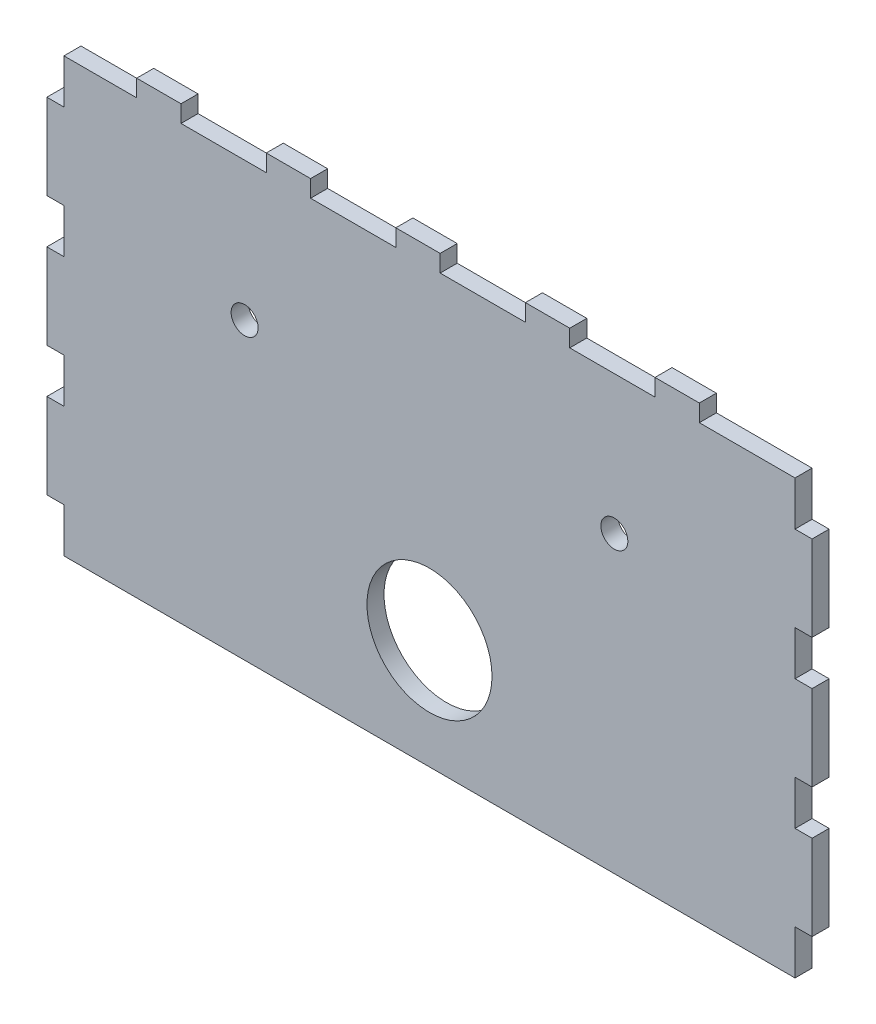
SolidWorks part; units mm, degrees
material "ENPH 253 Hardboard"
ref_plane "Front Plane" through (0, 0, 0) normal (0, 0, 1) x (1, 0, 0)
ref_plane "Top Plane" through (0, 0, 0) normal (0, 1, 0) x (1, 0, 0)
ref_plane "Right Plane" through (0, 0, 0) normal (1, 0, 0) x (0, 0, -1)
sketch "Sketch1" plane through (0, 0, 0) normal (0, 0, 1) x (1, 0, 0)
  line L1 (-67.32, 38.1) -> (67.32, 38.1)
  line L2 (-67.32, 38.1) -> (-67.32, -38.1)
  line L3 (-67.32, -38.1) -> (67.32, -38.1)
  line L4 (67.32, 38.1) -> (67.32, -38.1)
  line L5 (-67.32, 38.1) -> (67.32, -38.1) construction
  line L6 (-67.32, -38.1) -> (67.32, 38.1) construction
  point P0 (0, 0)
  dimension "D1" = 134.64
  dimension "D2" = 76.2
extrude "Boss-Extrude1" add sketch "Sketch1" along normal blind 3
sketch "Sketch2" plane through (0, 0, 3) normal (0, 0, 1) x (1, 0, 0)
  line L1 (-67.32, 38.1) -> (-64.32, 38.1)
  line L2 (-67.32, 38.1) -> (-67.32, 30.3)
  line L3 (-67.32, 30.3) -> (-64.32, 30.3)
  line L4 (-64.32, 38.1) -> (-64.32, 30.3)
  dimension "D1" = 3
  dimension "D2" = 7.8
extrude "Cut-Extrude1" cut sketch "Sketch2" against normal through all
pattern_linear "LPattern1" count 4 spacing 22.8 along (0, -1, 0) of "Cut-Extrude1"
mirror "Mirror4" about plane through (0, 0, 0) normal (1, 0, 0) of "LPattern1", "Cut-Extrude1"
sketch "Sketch3" plane through (0, 38.1, 0) normal (0, 1, 0) x (1, 0, 0)
  line L0 (64.32, 0) -> (-64.32, 0) construction
  line L1 (-43.72, 0) -> (-51.52, 0)
  line L2 (-43.72, 0) -> (-43.72, -3)
  line L3 (-43.72, -3) -> (-51.52, -3)
  line L4 (-51.52, 0) -> (-51.52, -3)
  line L5 (64.32, -3) -> (-64.32, -3) construction
  line L6 (-64.32, 0) -> (-64.32, -3) construction
  dimension "D1" = 12.8
  dimension "D2" = 7.8
extrude "Boss-Extrude2" add sketch "Sketch3" along normal blind 3
pattern_linear "LPattern2" count 5 spacing 22.8 along (1, 0, 0) of "Boss-Extrude2"
sketch "Sketch4" plane through (0, 0, 3) normal (0, 0, 1) x (1, 0, 0)
  line L0 (-64.32, -38.1) -> (64.32, -38.1) construction
  line L1 (-64.32, -38.1) -> (-64.32, -30.3) construction
  circle A0 centre (0, -18.8) radius 11
  dimension "D1" = 22
  dimension "D2" = 19.3
  dimension "D3" = 64.32
extrude "Cut-Extrude2" cut sketch "Sketch4" against normal through all
sketch "Sketch5" plane through (0, 0, 3) normal (0, 0, 1) x (1, 0, 0)
  line L0 (0, -18.8) -> (-36.8059, -18.8) construction
  line L1 (-32.5269, 13.7269) -> (0, -18.8) construction
  line L2 (0, -18.8) -> (32.5269, 13.7269) construction
  circle A0 centre (32.5269, 13.7269) radius 2.3749
  circle A1 centre (-32.5269, 13.7269) radius 2.3749
  dimension "D1" = 4.7498
  dimension "D2" = 4.7498
  dimension "D3" = 46
  dimension "D4" = 46
  dimension "D5" = 45
  dimension "D6" = 90
extrude "Cut-Extrude3" cut sketch "Sketch5" against normal through all
